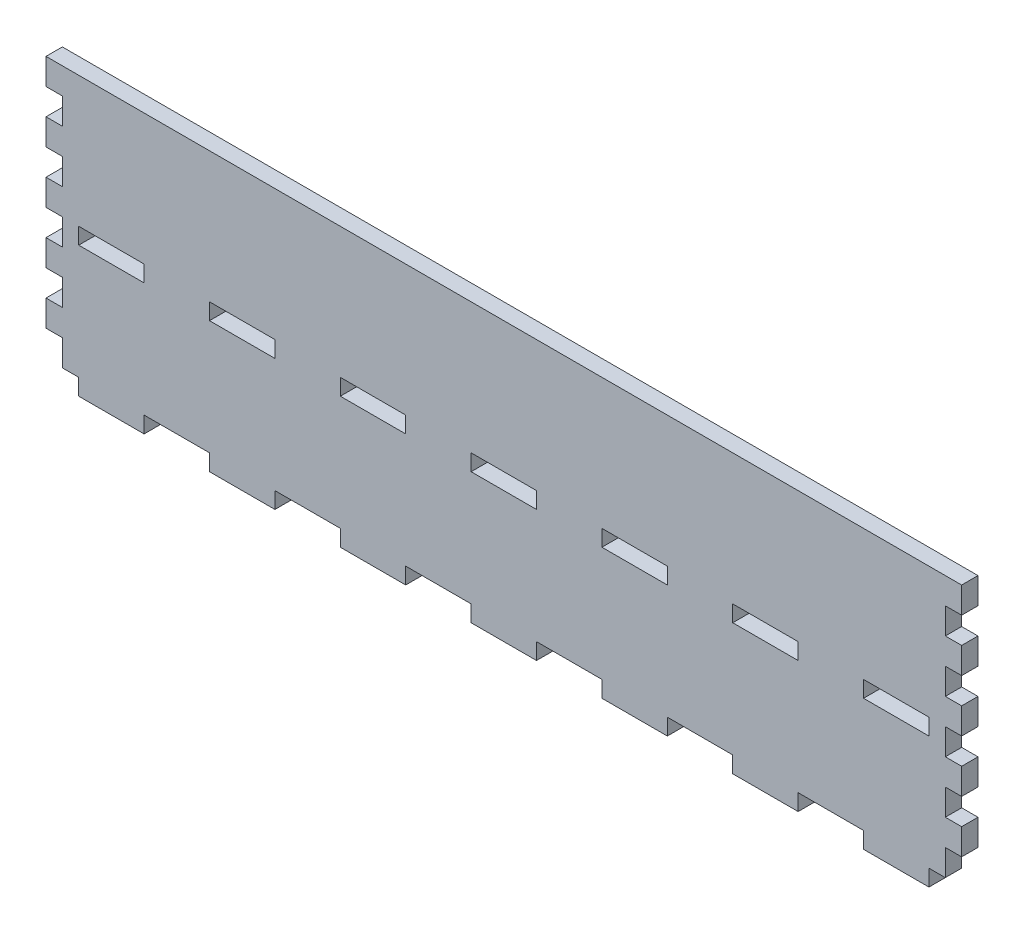
SolidWorks part; units mm, degrees
material "Pin"
ref_plane "Front" through (0, 0, 0) normal (0, 0, 1) x (1, 0, 0)
ref_plane "Top" through (0, 0, 0) normal (0, 1, 0) x (1, 0, 0)
ref_plane "Right" through (0, 0, 0) normal (1, 0, 0) x (0, 0, -1)
sketch "Esquisse1" plane through (0, 0, 0) normal (0, 0, 1) x (1, 0, 0)
  line L1 (-177.8, 53.975) -> (177.8, 53.975)
  line L2 (-177.8, 53.975) -> (-177.8, -53.975)
  line L3 (-177.8, -53.975) -> (177.8, -53.975)
  line L4 (177.8, 53.975) -> (177.8, -53.975)
  line L5 (-177.8, 53.975) -> (177.8, -53.975) construction
  line L6 (-177.8, -53.975) -> (177.8, 53.975) construction
  point P0 (0, 0)
  dimension "D1" = 355.6
  dimension "D2" = 107.95
extrude "Boss.-Extru.1" add sketch "Esquisse1" along normal blind 6.35
sketch "Esquisse4" plane through (0, 0, 6.35) normal (0, 0, 1) x (1, 0, 0)
  line L0 (-177.8, 53.975) -> (-177.8, -53.975) construction
  line L1 (-177.8, 43.815) -> (-171.45, 43.815)
  line L2 (-177.8, 43.815) -> (-177.8, 33.655)
  line L3 (-177.8, 33.655) -> (-171.45, 33.655)
  line L4 (-171.45, 43.815) -> (-171.45, 33.655)
  line L5 (177.8, 53.975) -> (-177.8, 53.975) construction
  dimension "D1" = 6.35
  dimension "D2" = 10.16
  dimension "D3" = 10.16
extrude "Enlèv. mat.-Extru.3" cut sketch "Esquisse4" against normal blind 6.35
pattern_linear "Répétition linéaire2" count 5 spacing 20.32 along (0, -1, 0) count 2 spacing 349.25 along (1, 0, 0) of "Enlèv. mat.-Extru.3"
sketch "Esquisse5" plane through (0, 0, 6.35) normal (0, 0, 1) x (1, 0, 0)
  line L0 (-177.8, -53.975) -> (177.8, -53.975) construction
  line L1 (-139.7, -53.975) -> (-114.3, -53.975)
  line L2 (-139.7, -53.975) -> (-139.7, -47.625)
  line L3 (-139.7, -47.625) -> (-114.3, -47.625)
  line L4 (-114.3, -53.975) -> (-114.3, -47.625)
  line L5 (-177.8, -47.625) -> (-177.8, -53.975) construction
  dimension "D1" = 6.35
  dimension "D2" = 25.4
  dimension "D3" = 38.1
extrude "Enlèv. mat.-Extru.4" cut sketch "Esquisse5" against normal blind 6.35
pattern_linear "Répétition linéaire3" count 7 spacing 50.8 along (1, 0, 0) of "Enlèv. mat.-Extru.4"
sketch "Esquisse6" plane through (0, 0, 6.35) normal (0, 0, 1) x (1, 0, 0)
  line L1 (-177.8, -53.975) -> (-165.1, -53.975)
  line L2 (-177.8, -53.975) -> (-177.8, -47.625)
  line L3 (-177.8, -47.625) -> (-165.1, -47.625)
  line L4 (-165.1, -53.975) -> (-165.1, -47.625)
  dimension "D1" = 6.35
  dimension "D2" = 12.7
extrude "Enlèv. mat.-Extru.5" cut sketch "Esquisse6" against normal blind 6.35
sketch "Esquisse7" plane through (0, 0, 6.35) normal (0, 0, 1) x (1, 0, 0)
  line L0 (-171.45, 13.335) -> (-171.45, 23.495) construction
  line L1 (-165.1, 3.175) -> (-139.7, 3.175)
  line L2 (-165.1, 3.175) -> (-165.1, -3.175)
  line L3 (-165.1, -3.175) -> (-139.7, -3.175)
  line L4 (-139.7, 3.175) -> (-139.7, -3.175)
  line L5 (-114.3, -47.625) -> (-139.7, -47.625) construction
  dimension "D1" = 6.35
  dimension "D2" = 25.4
  dimension "D3" = 6.35
  dimension "D4" = 44.45
extrude "Enlèv. mat.-Extru.6" cut sketch "Esquisse7" against normal blind 6.35
pattern_linear "Répétition linéaire5" count 7 spacing 50.8 along (1, 0, 0) of "Enlèv. mat.-Extru.6"
sketch "Esquisse8" plane through (0, 0, 6.35) normal (0, 0, 1) x (1, 0, 0)
  line L0 (-114.3, -47.625) -> (-139.7, -47.625) construction
  line L3 (-171.45, -47.625) -> (-171.45, -37.465) construction
  circle A1 centre (107.95, -28.575) radius 9.525
  circle A2 centre (-120.65, -28.575) radius 9.525
  point P0 (0, 0)
  dimension "D1" = 19.05
  dimension "D2" = 228.6
  dimension "D4" = 19.05
  dimension "D5" = 50.8
extrude "Enlèv. mat.-Extru.7" [suppressed] cut sketch "Esquisse8" against normal blind 6.35
sketch "Esquisse9" plane through (0, 0, 6.35) normal (0, 0, 1) x (1, 0, 0)
  line L1 (12.7, 3.175) -> (-12.7, 3.175) construction
  text T0 "<b>1</b>" font "Britannic Bold" height 19.05
  text T1 "<b>2</b>" font "Britannic Bold" height 19.05
  text T2 "<b>3</b>" font "Britannic Bold" height 19.05
  dimension "D1" = 6.35
  dimension "D2" = 19.05
  dimension "D3" = 114.3
  dimension "D4" = 114.3
